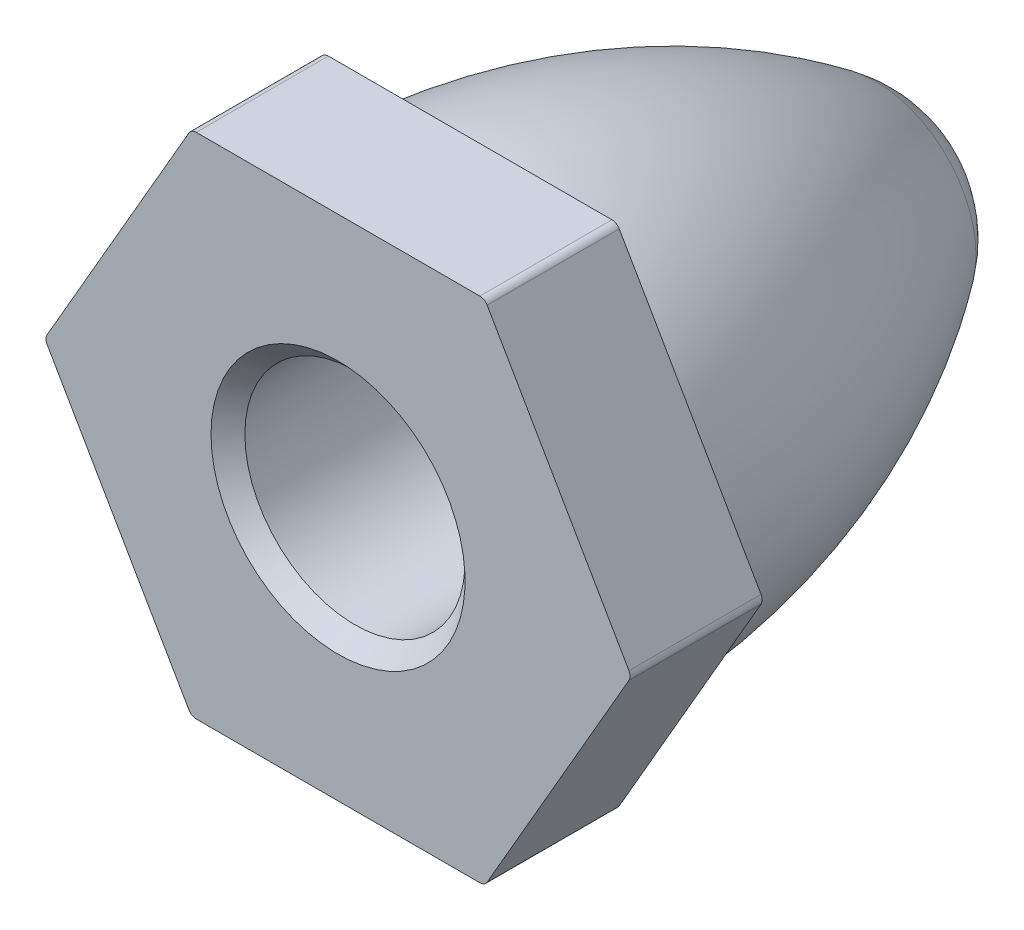
SolidWorks part; units mm, degrees
ref_plane "Plan de face" through (0, 0, 0) normal (0, 0, 1) x (1, 0, 0)
ref_plane "Plan de dessus" through (0, 0, 0) normal (0, 1, 0) x (1, 0, 0)
ref_plane "Plan de droite" through (0, 0, 0) normal (1, 0, 0) x (0, 0, -1)
sketch "Esquisse2" plane through (0, 0, 0) normal (0, 0, 1) x (1, 0, 0)
  line L0 (0, 0) -> (6.9282, 0) construction
  line L1 (6.9282, 0) -> (3.4641, 6)
  line L2 (3.4641, 6) -> (-3.4641, 6)
  line L3 (-3.4641, 6) -> (-6.9282, 0)
  line L4 (6.9282, 0) -> (3.4641, -6)
  line L5 (3.4641, -6) -> (-3.4641, -6)
  line L6 (-3.4641, -6) -> (-6.9282, 0)
  circle A0 centre (0, 0) radius 6.9282 construction
  circle A1 centre (0, 0) radius 2.6
  dimension "D2" = 5.2
  dimension "D1" = 12
extrude "Extrusion1" add sketch "Esquisse2" along normal blind 3.12
sketch "Esquisse3" plane through (0, 0, 0) normal (0, 1, 0) x (1, 0, 0)
  line L0 (0, 0) -> (0, 10.78) construction
  line L1 (0, 10.78) -> (-2.5556, 10.78) construction
  line L2 (3.4641, -3.12) -> (-3.4641, -3.12) construction
  line L3 (6.9282, 0) -> (3.4641, 0) construction
  line L4 (5.5, 0) -> (5.5, 13.6325) construction
  line L5 (5.5, 0) -> (0, 0)
  line L6 (0, 0) -> (0, 10.78)
  arc A0 (0, 10.78) -> (2.3666, 9.58) centre (0, 7.8464) cw
  arc A1 (2.3666, 9.58) -> (5.5, 0) centre (-10.7114, 0) cw
  dimension "D2" = 11
  dimension "D1" = 13.9
  dimension "D3" = 1.2
revolve "Révolution1" add sketch "Esquisse3" angle 360 about L6
sketch "Esquisse4" plane through (0, 0, 3.12) normal (0, 0, 1) x (1, 0, 0)
  circle A0 centre (0, 0) radius 2.6 construction
  circle A1 centre (0, 0) radius 2.6
extrude "Extrusion2" cut sketch "Esquisse4" against normal blind 10
fillet "Congé1" radius 0.2 6 edges at (-3.4641, -6, 1.56) (3.4641, -6, 1.56) (-6.9282, 0, 1.56) (6.9282, 0, 1.56) (3.4641, 6, 1.56) (-3.4641, 6, 1.56)
chamfer "Chanfrein1" distance 0.4 angle 45 1 edges at (2.6, 0, 3.12)
